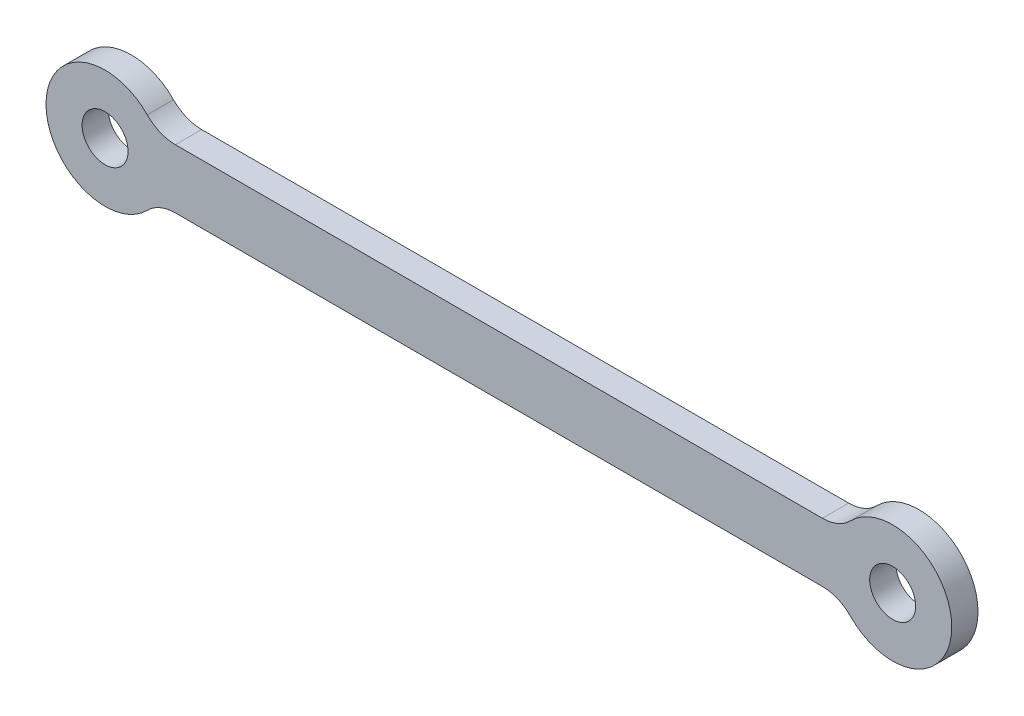
SolidWorks part; units mm, degrees
ref_plane "Front Plane" through (0, 0, 0) normal (0, 0, 1) x (1, 0, 0)
ref_plane "Top Plane" through (0, 0, 0) normal (0, 1, 0) x (1, 0, 0)
ref_plane "Right Plane" through (0, 0, 0) normal (1, 0, 0) x (0, 0, -1)
sketch "Sketch1" plane through (0, 0, 0) normal (0, 0, 1) x (1, 0, 0)
  line L2 (5.3561, 2.25) -> (54.6439, 2.25)
  line L3 (3.8971, 2.25) -> (3.8971, -2.25) construction
  line L4 (54.6439, -2.25) -> (5.3561, -2.25)
  line L5 (56.1029, 2.25) -> (56.1029, -2.25) construction
  circle A8 centre (0, 0) radius 1.75
  arc A9 (3.2136, 3.15) -> (3.2136, -3.15) centre (0, 0) ccw
  circle A10 centre (60, 0) radius 1.75
  arc A11 (56.7864, -3.15) -> (56.7864, 3.15) centre (60, 0) ccw
  arc A12 (56.7864, -3.15) -> (54.6439, -2.25) centre (54.6439, -5.25) ccw
  arc A13 (54.6439, 2.25) -> (56.7864, 3.15) centre (54.6439, 5.25) ccw
  arc A14 (5.3561, -2.25) -> (3.2136, -3.15) centre (5.3561, -5.25) ccw
  arc A15 (5.3561, 2.25) -> (3.2136, 3.15) centre (5.3561, 5.25) cw
  dimension "D3" = 4.5
  dimension "D5" = 3.5
  dimension "D6" = 3.5
  dimension "D7" = 4.5
  dimension "D9" = 3
  dimension "D2" = 4.5
  dimension "D8" = 60
extrude "Boss-Extrude1" add sketch "Sketch1" along normal blind 2
